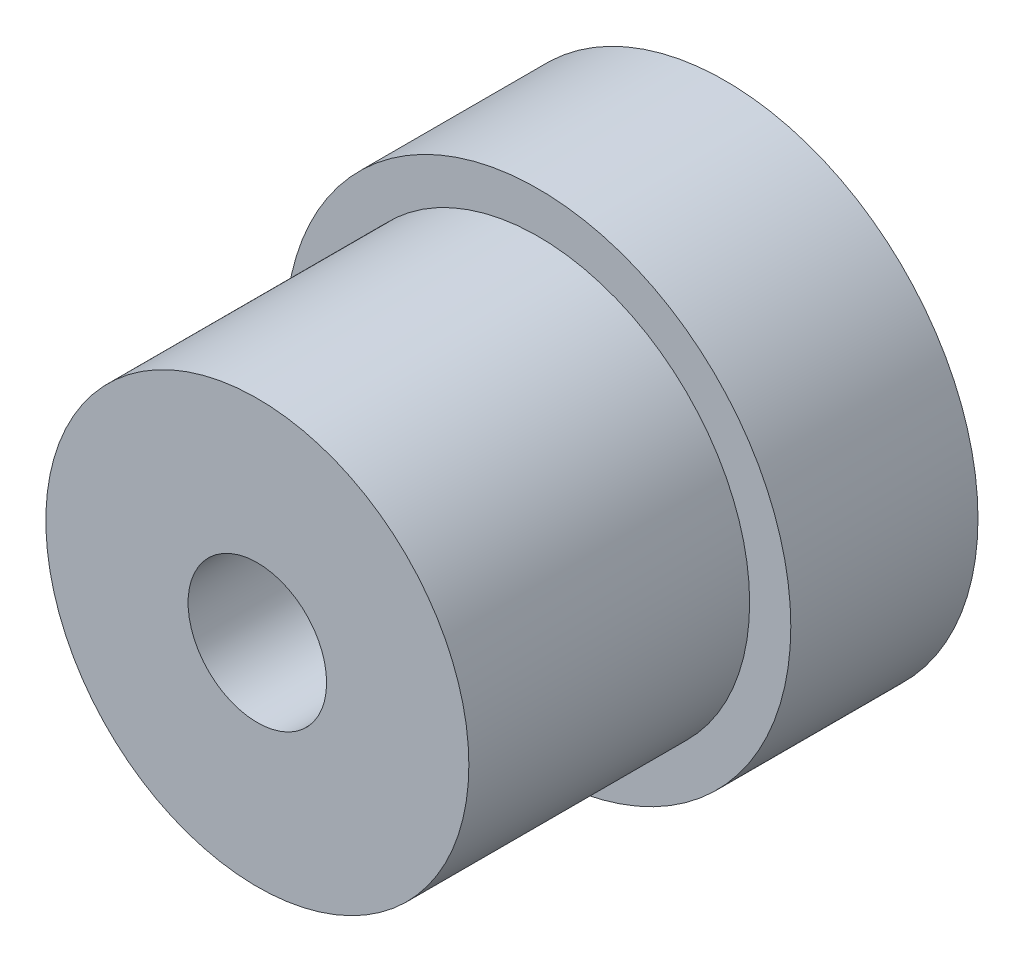
SolidWorks part; units mm, degrees
ref_plane "前视基准面" through (0, 0, 0) normal (0, 0, 1) x (1, 0, 0)
ref_plane "上视基准面" through (0, 0, 0) normal (0, 1, 0) x (1, 0, 0)
ref_plane "右视基准面" through (0, 0, 0) normal (1, 0, 0) x (0, 0, -1)
other "Configuration Table"
sketch "AICAD_SKETCH_F001" plane through (0, 0, 0) normal (0, 0, 1) x (1, 0, 0)
  circle A0 centre (0, 0) radius 13.5
  point P0 (0, 0)
  dimension "D1" = 13.5
extrude "AICAD_F001_BASE_EXTRUDE" add sketch "AICAD_SKETCH_F001" along normal blind 10
sketch "AICAD_SKETCH_F002" plane through (0, 0, 10) normal (0, 0, 1) x (1, 0, 0)
  circle A0 centre (0, 0) radius 11.3
  point P0 (0, 0)
  dimension "D1" = 11.3
extrude "AICAD_F002_BOSS_EXTRUDE" add sketch "AICAD_SKETCH_F002" along normal blind 15
sketch "AICAD_SKETCH_F003" plane through (0, 0, 25) normal (0, 0, 1) x (1, 0, 0)
  circle A0 centre (0, 0) radius 3.7
  point P0 (0, 0)
  dimension "D1" = 3.7
extrude "AICAD_F003_CUT_EXTRUDE" cut sketch "AICAD_SKETCH_F003" against normal through all
